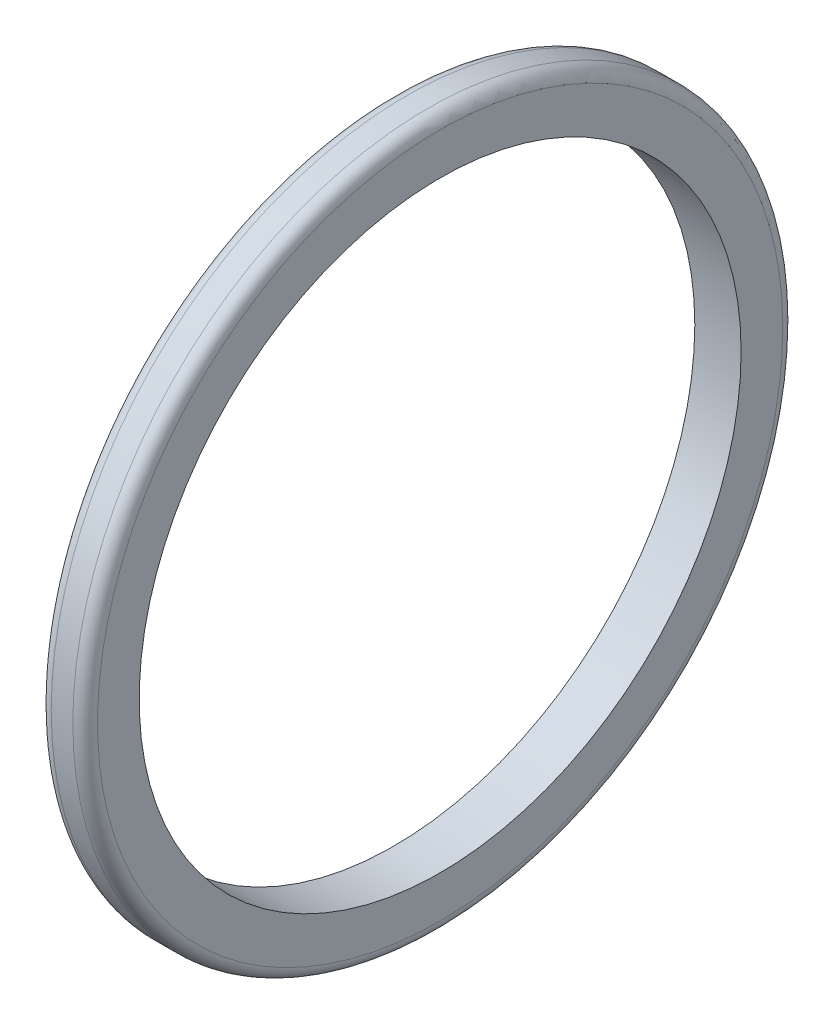
SolidWorks part; units mm, degrees
ref_plane "Front Plane" through (0, 0, 0) normal (0, 0, 1) x (1, 0, 0)
ref_plane "Top Plane" through (0, 0, 0) normal (0, 1, 0) x (1, 0, 0)
ref_plane "Right Plane" through (0, 0, 0) normal (1, 0, 0) x (0, 0, -1)
sketch "Sketch1" plane through (0, 0, 0) normal (1, 0, 0) x (0, 0, -1)
  circle A0 centre (0, 0) radius 230
  dimension "D1" = 460
extrude "Boss-Extrude1" add sketch "Sketch1" along normal blind 30 contours A0
fillet "Fillet1" radius 8 2 edges at (0, 0, -230) (30, 0, -230)
sketch "Sketch2" plane through (30, 0, 0) normal (1, 0, 0) x (0, 0, -1)
  circle A0 centre (0, 0) radius 195
  dimension "D1" = 390
extrude "Cut-Extrude1" cut sketch "Sketch2" against normal through all
